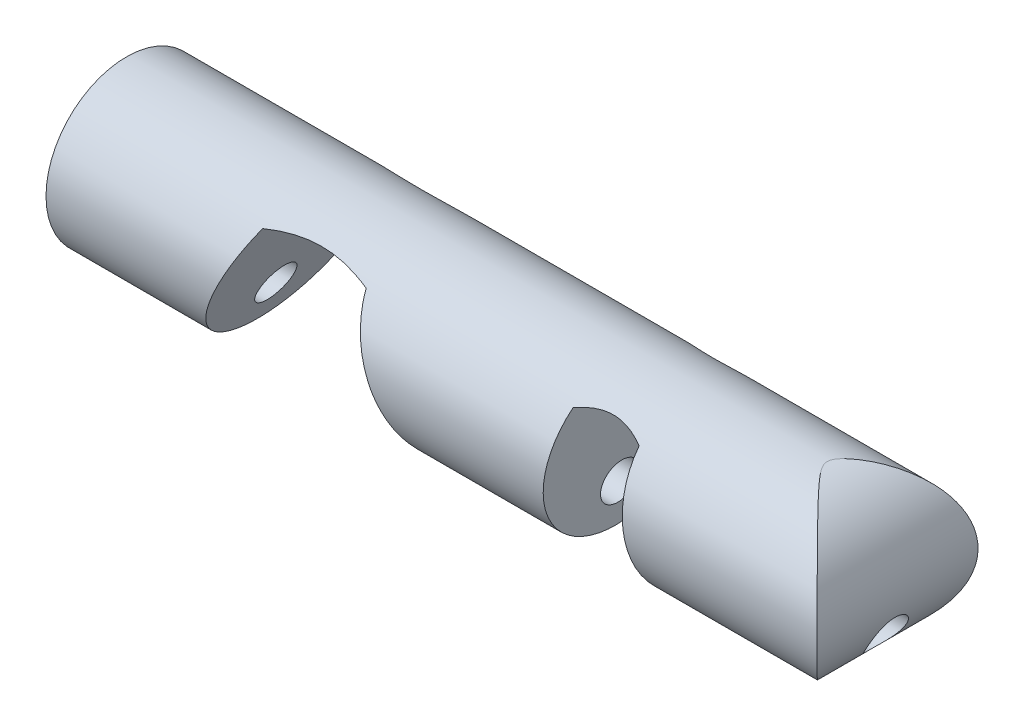
SolidWorks part; units mm, degrees
material "ABS"
ref_plane "Front Plane" through (0, 0, 0) normal (0, 0, 1) x (1, 0, 0)
ref_plane "Top Plane" through (0, 0, 0) normal (0, 1, 0) x (1, 0, 0)
ref_plane "Right Plane" through (0, 0, 0) normal (1, 0, 0) x (0, 0, -1)
sketch "Sketch1" plane through (0, 0, 0) normal (0, 0, 1) x (1, 0, 0)
  line L0 (0, 0) -> (14.2672, 0)
  line L1 (0, 0) -> (0, 17.52)
  line L2 (0, 17.52) -> (73.8895, 17.52)
  line L10 (38.9495, 0) -> (53.2194, -0.0415)
  line L17 (63.8895, 0) -> (73.8895, 0)
  line L27 (14.2672, 0) -> (21.021, 14.9436)
  line L28 (38.9495, 0) -> (32.2752, 14.9436)
  line L33 (54.7821, 14.9436) -> (53.2194, -0.0415)
  line L34 (61.9703, 14.9436) -> (63.8895, 0)
  arc A0 (21.021, 14.9436) -> (32.2752, 14.9436) centre (26.6481, -6.7689) cw
  arc A2 (54.7821, 14.9436) -> (61.9703, 14.9436) centre (58.3762, 6.2981) cw
  arc A3 (73.8895, 17.52) -> (73.8895, 0) centre (75.0526, 8.76) cw
  point P18 (83.8895, -0.0769)
  point P20 (0, 0)
  point P21 (83.8895, 17.52)
  point P22 (74.0608, 17.541)
  point P23 (0, 0)
  point P24 (74.3367, -0.0478)
  dimension "D8" = 22.4298
  dimension "D3" = 9.3628
  dimension "D15" = 8.8369
  dimension "D2" = 17.52
  dimension "D4" = 14.2672
  dimension "D5" = 14.27
  dimension "D6" = 75.0526
  dimension "D7" = 21.021
  dimension "D9" = 26.6481
  dimension "D10" = 48.388
  dimension "D11" = 38.9495
  dimension "D12" = 53.2194
  dimension "D13" = 54.7821
  dimension "D14" = 58.3762
extrude "Boss-Extrude3" add sketch "Sketch1" along normal blind 17.52 contours L0 L27 A0 L28 L10 L33 A2 L34 L17 A3 L2 L1
sketch "Sketch5" plane through (0, 0, 0) normal (-1, 0, 0) x (0, 0, 1)
  line L0 (8.76, 8.76) -> (0.005, 8.76) construction
  line L1 (0, 0) -> (0, 17.52) construction
  line L2 (17.52, 0) -> (0, 0) construction
  circle A0 centre (8.76, 8.76) radius 8.755
  dimension "D1" = 17.51
  dimension "D2" = 8.76
  dimension "D3" = 8.76
extrude "Cut-Extrude7" cut sketch "Sketch5" against normal through all flip side to cut
sketch "Sketch6" plane through (0, 0, 0) normal (-1, 0, 0) x (0, 0, 1)
  line L0 (8.76, 17.515) -> (8.76, 0.005) construction
  circle A2 centre (8.76, 4.385) radius 2.1003
  circle A3 centre (8.76, 8.76) radius 8.755 construction
  dimension "D2" = 4.2007
  dimension "D1" = 4.375
extrude "Cut-Extrude8" cut sketch "Sketch6" against normal through all contours A2
